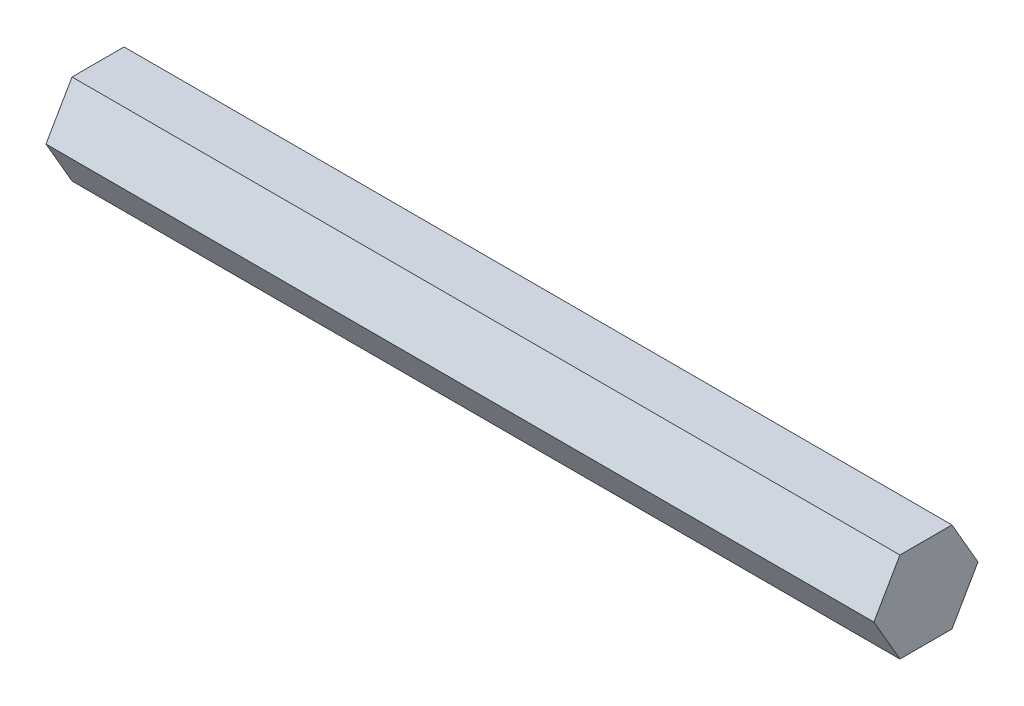
SolidWorks part; units mm, degrees
ref_plane "Front Plane" through (0, 0, 0) normal (0, 0, 1) x (1, 0, 0)
ref_plane "Top Plane" through (0, 0, 0) normal (0, 1, 0) x (1, 0, 0)
ref_plane "Right Plane" through (0, 0, 0) normal (1, 0, 0) x (0, 0, -1)
sketch "Sketch1" plane through (0, 0, 0) normal (1, 0, 0) x (0, 0, -1)
  line L1 (2.829, 0) -> (1.4145, 2.45)
  line L2 (1.4145, 2.45) -> (-1.4145, 2.45)
  line L3 (-1.4145, 2.45) -> (-2.829, 0)
  line L4 (-2.829, 0) -> (-1.4145, -2.45)
  line L5 (-1.4145, -2.45) -> (1.4145, -2.45)
  line L6 (1.4145, -2.45) -> (2.829, 0)
  circle A0 centre (0, 0) radius 2.45 construction
  dimension "D1" = 4.9
extrude "Boss-Extrude1" add sketch "Sketch1" along normal blind 45
